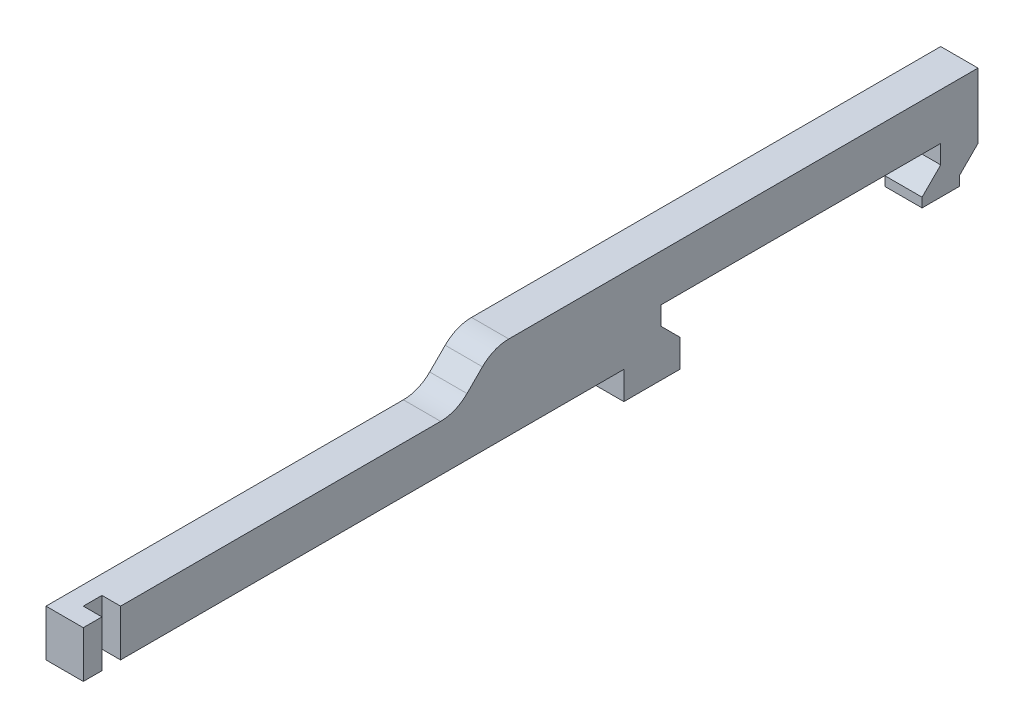
SolidWorks part; units mm, degrees
ref_plane "Спереди" through (0, 0, 0) normal (0, 0, 1) x (1, 0, 0)
ref_plane "Сверху" through (0, 0, 0) normal (0, 1, 0) x (1, 0, 0)
ref_plane "Справа" through (0, 0, 0) normal (1, 0, 0) x (0, 0, -1)
sketch "Эскиз1" plane through (0, 0, 0) normal (1, 0, 0) x (0, 0, -1)
  line L0 (20, 2.5) -> (22, 4.5)
  line L1 (0, 0) -> (20, 0)
  line L2 (0, 0) -> (0, 2.5)
  line L3 (0, 2.5) -> (20, 2.5)
  line L4 (20, 0) -> (20, 2.5)
  line L5 (22, 4.5) -> (22, 2.5) construction
  line L6 (22, 2.5) -> (20, 2.5) construction
  line L7 (22, 4.5) -> (29, 4.5)
  line L8 (20, 0) -> (29, 0)
  line L9 (29, 0) -> (29, -1.5)
  line L10 (29, -1.5) -> (32, -1.5)
  line L11 (32, -1.5) -> (32, 0)
  line L12 (32, 0) -> (31, 1)
  line L13 (31, 1) -> (31, 2)
  line L14 (31, 2) -> (46, 2)
  line L15 (32, 0) -> (31, 0) construction
  line L16 (31, 0) -> (31, 1) construction
  line L17 (38.5, 2) -> (38.5, 1) construction
  line L18 (45, 0) -> (46, 1)
  line L19 (46, 1) -> (46, 2)
  line L20 (45, 0) -> (45, -0.5)
  line L21 (45, -0.5) -> (47, -0.5)
  line L22 (47, -0.5) -> (47, 0)
  line L23 (47, 0) -> (48, 1)
  line L24 (48, 1) -> (48, 4.5)
  line L25 (48, 4.5) -> (29, 4.5)
  dimension "D1" = 2.5
  dimension "D2" = 20
  dimension "D3" = 2
  dimension "D4" = 2
  dimension "D5" = 7
  dimension "D6" = 9
  dimension "D7" = 1.5
  dimension "D8" = 3
  dimension "D9" = 1.5
  dimension "D10" = 1
  dimension "D11" = 1
  dimension "D12" = 1
  dimension "D13" = 15
  dimension "D14" = 0.5
  dimension "D15" = 2
extrude "Бобышка-Вытянуть1" add sketch "Эскиз1" along normal blind 2 contours L24 L25 L7 L0 L4 L8 L9 L10 L11 L12 L13 L14 L19 L18 L20 L21 L22 L23 | L1 L4 L3 L2
fillet "Скругление1" radius 2 2 edges at (1, 4.5, -22) (1, 2.5, -20)
sketch "Эскиз2" plane through (0, 2.5, 0) normal (0, 1, 0) x (1, 0, 0)
  line L0 (2, 0) -> (2, 1) construction
  line L1 (2, 0) -> (2, 19.1716) construction
  line L3 (2, 1) -> (1, 1)
  line L4 (2, 1) -> (2, 2)
  line L5 (2, 2) -> (1, 2)
  line L6 (1, 1) -> (1, 2)
  dimension "D1" = 1
  dimension "D2" = 1
  dimension "D3" = 1
extrude "Вырез-Вытянуть1" cut sketch "Эскиз2" against normal through all
